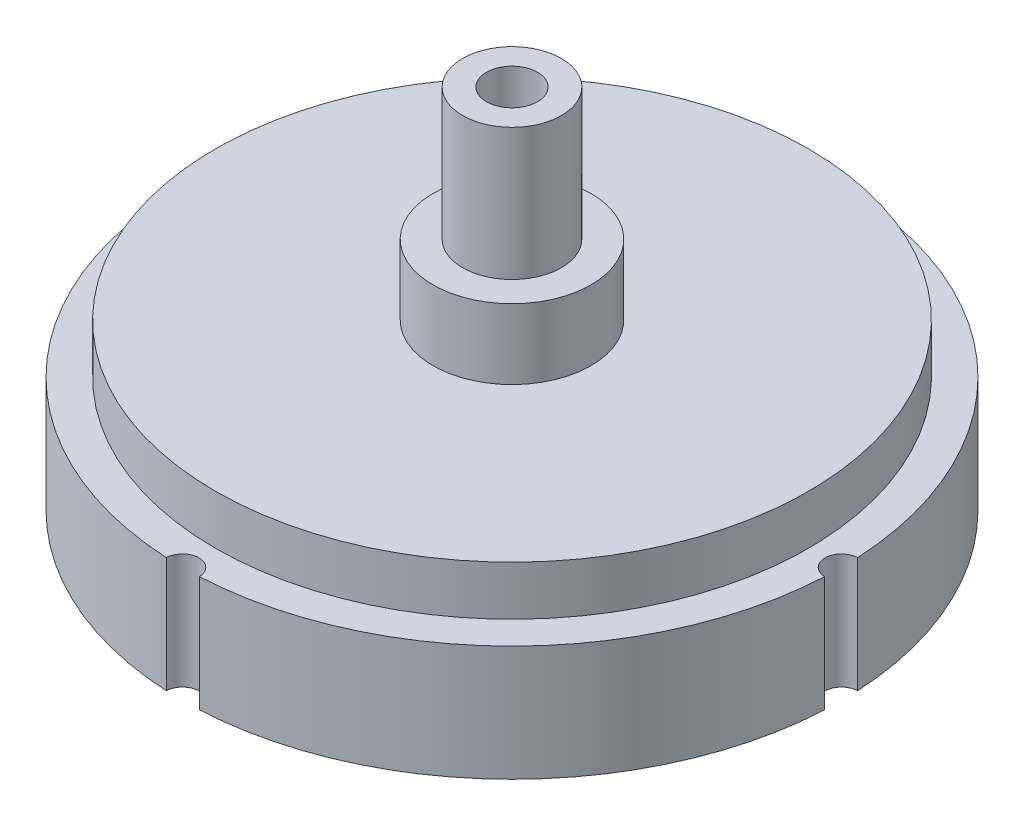
SolidWorks part; units mm, degrees
material "AISI 316 Stainless Steel Sheet (SS)"
ref_plane "Front Plane" through (0, 0, 0) normal (0, 0, 1) x (1, 0, 0)
ref_plane "Top Plane" through (0, 0, 0) normal (0, 1, 0) x (1, 0, 0)
ref_plane "Right Plane" through (0, 0, 0) normal (1, 0, 0) x (0, 0, -1)
sketch "Sketch4" plane through (0, 0, 0) normal (0, 0, 1) x (1, 0, 0)
  line L0 (0, 0) -> (0, 17.9621) construction
  line L1 (-0.775, 11.125) -> (-0.775, 4)
  line L2 (-1.2, 0) -> (-10, 0)
  line L3 (-10, 0) -> (-10, 3.5)
  line L4 (-9, 5) -> (-2.4, 5)
  line L5 (-2.4, 5) -> (-2.4, 7.125)
  line L6 (-2.4, 7.125) -> (-1.5, 7.125)
  line L7 (-1.5, 7.125) -> (-1.5, 11.125)
  line L8 (-1.5, 11.125) -> (-0.775, 11.125)
  line L9 (-10, 3.5) -> (-9, 3.5)
  line L10 (-9, 3.5) -> (-9, 5)
  line L11 (-1.2, 0) -> (-1.2, 4)
  line L12 (-1.2, 4) -> (-0.775, 4)
  dimension "D1" = 0.775
  dimension "D2" = 1.5
  dimension "D3" = 4
  dimension "D4" = 2.125
  dimension "D5" = 0.9
  dimension "D6" = 10
  dimension "D7" = 5
  dimension "D8" = 1.5
  dimension "D9" = 1
  dimension "D10" = 4
  dimension "D11" = 1.2
revolve "Revolve1" add sketch "Sketch4" angle 360 about L0
sketch "Sketch5" plane through (0, 0, 0) normal (0, -1, 0) x (1, 0, 0)
  circle A0 centre (0, 10) radius 0.5
  circle A1 centre (0, 0) radius 10 construction
  circle A2 centre (10, 0) radius 0.5
  circle A3 centre (0, -10) radius 0.5
  circle A4 centre (-10, 0) radius 0.5
  dimension "D1" = 1
extrude "Cut-Extrude1" cut sketch "Sketch5" against normal through all both and the other way through all
